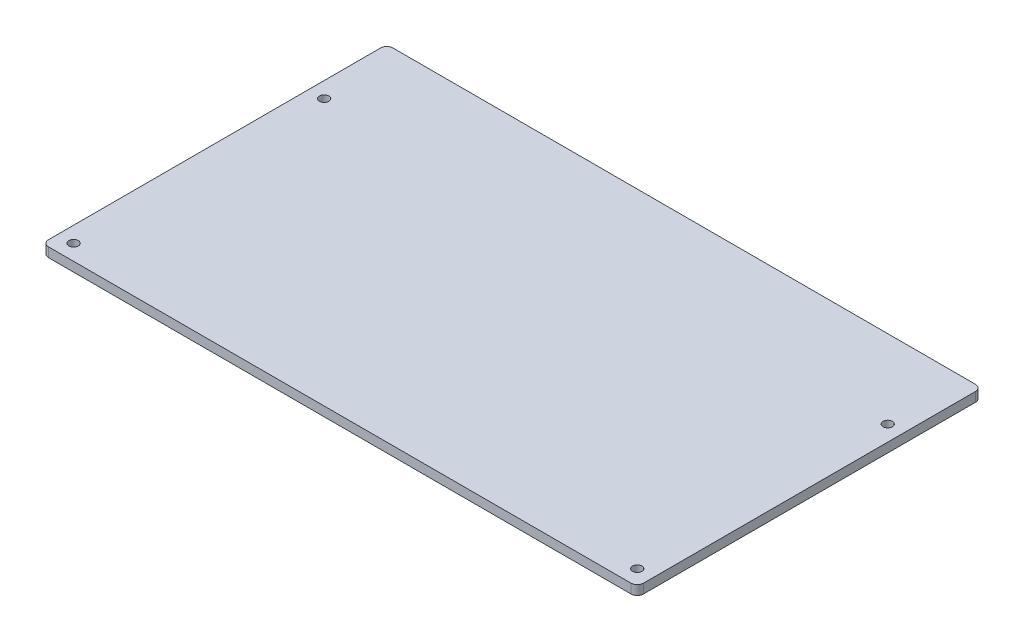
SolidWorks part; units mm, degrees
material "6061 Alloy"
ref_plane "Front Plane" through (0, 0, 0) normal (0, 0, 1) x (1, 0, 0)
ref_plane "Top Plane" through (0, 0, 0) normal (0, 1, 0) x (1, 0, 0)
ref_plane "Right Plane" through (0, 0, 0) normal (1, 0, 0) x (0, 0, -1)
sketch "Sketch1" plane through (0, 0, 0) normal (0, 1, 0) x (1, 0, 0)
  line L0 (-95, -55) -> (95, 55) construction
  line L1 (-95, 55) -> (95, 55)
  line L2 (-95, 55) -> (-95, -55)
  line L3 (-95, -55) -> (95, -55)
  line L4 (95, 55) -> (95, -55)
  point P4 (0, 0)
  dimension "D1" = 190
  dimension "D2" = 110
extrude "Boss-Extrude1" add sketch "Sketch1" along normal blind 3
sketch "Sketch2" plane through (0, 3, 0) normal (0, 1, 0) x (1, 0, 0)
  line L0 (-95, 55) -> (-95, -55) construction
  line L1 (-95, -55) -> (95, -55) construction
  line L2 (95, -55) -> (95, 55) construction
  line L3 (90, 30) -> (90, -50) construction
  line L4 (-90, 30) -> (-90, -50) construction
  circle A0 centre (-90, -50) radius 1.5
  circle A1 centre (-90, 30) radius 1.5
  circle A2 centre (90, 30) radius 1.5
  circle A3 centre (90, -50) radius 1.5
  circle A4 centre (-90, -10) radius 1.5 construction
  circle A5 centre (90, -10) radius 1.5 construction
  dimension "D2" = 3
  dimension "D1" = 5
  dimension "D3" = 5
  dimension "D4" = 5
  dimension "D5" = 80
extrude "Cut-Extrude1" cut sketch "Sketch2" against normal through all
fillet "Fillet1" radius 2 4 edges at (95, 1.5, 55) (95, 1.5, -55) (-95, 1.5, 55) (-95, 1.5, -55)
